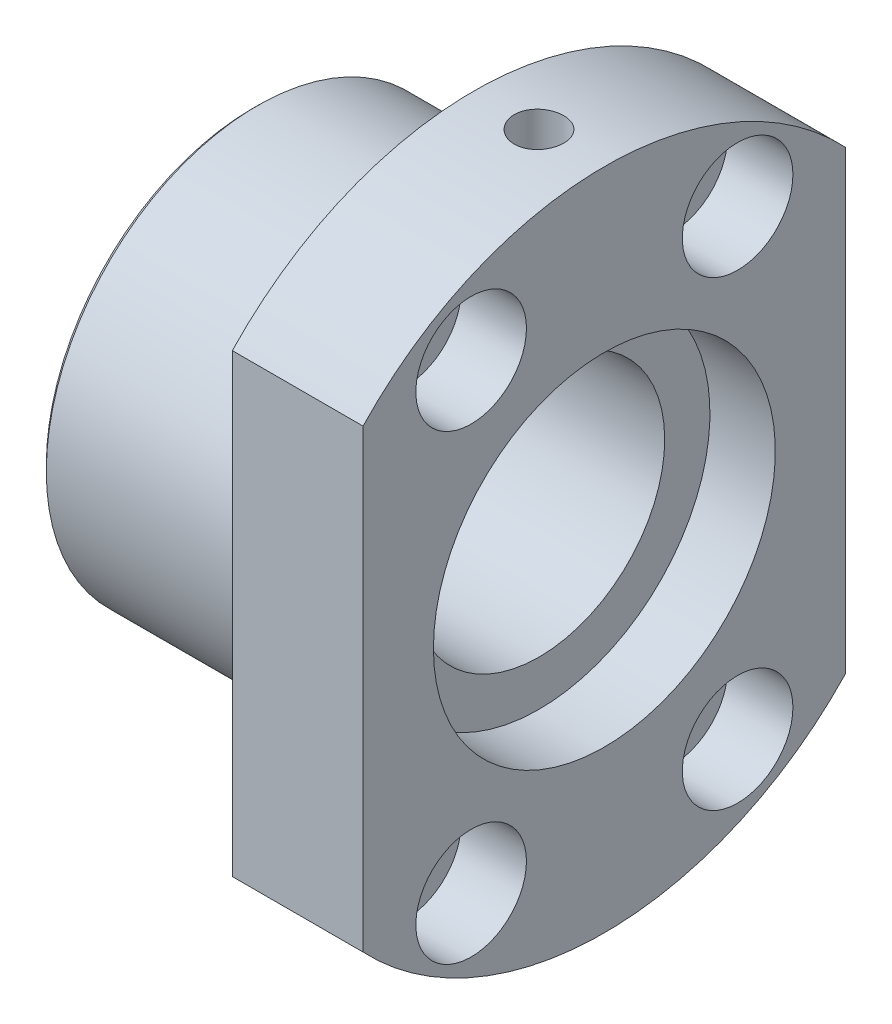
SolidWorks part; units mm, degrees
ref_plane "Front Plane" through (0, 0, 0) normal (0, 0, 1) x (1, 0, 0)
ref_plane "Top Plane" through (0, 0, 0) normal (0, 1, 0) x (1, 0, 0)
ref_plane "Right Plane" through (0, 0, 0) normal (1, 0, 0) x (0, 0, -1)
sketch "Sketch1" plane through (0, 0, 0) normal (0, 0, 1) x (1, 0, 0)
  line L0 (6.5, 17) -> (6.5, 12.5)
  line L1 (-22, 0) -> (13, 0) construction
  line L3 (-17, 12.5) -> (6.5, 12.5)
  line L4 (13, 33) -> (0, 33)
  line L5 (0, 33) -> (0, 21)
  line L6 (0, 21) -> (-22, 21)
  line L8 (-22, 21) -> (-22, 17)
  line L9 (-22, 17) -> (-17, 17)
  line L10 (-17, 17) -> (-17, 12.5)
  line L11 (6.5, 17) -> (13, 17)
  line L12 (13, 17) -> (13, 33)
revolve "Revolve1" add sketch "Sketch1" angle 360 about L1
sketch "Sketch2" plane through (0, 0, 0) normal (1, 0, 0) x (0, 0, -1)
  line L0 (24, 22.6495) -> (24, -22.6495)
  line L1 (-24, 22.6495) -> (-24, -22.6495)
  arc A0 (24, -22.6495) -> (24, 22.6495) centre (0, 0) ccw
  arc A2 (-24, 22.6495) -> (-24, -22.6495) centre (0, 0) ccw
extrude "Cut-Extrude1" cut sketch "Sketch2" along normal through all
hole_wizard "Socket Head Cap Screw1" positions "Sketch4" profile "Sketch3" counterbore size "M2" standard "JIS" end condition through all
sketch "Sketch4" plane through (13, 0, 0) normal (1, 0, 0) x (0, 0, -1)
  point P5 (-13.25, 22.9497)
  point P6 (13.25, -22.9497)
  point P7 (-13.25, -22.9497)
  point P8 (13.25, 22.9497)
sketch "Sketch3" plane through (13, 22.9497, 13.25) normal (0, 1, 0) x (0, 0, -1)
  line L0 (0, 0) -> (0, 35)
  line L1 (0, 35) -> (3.3, 35)
  line L3 (3.3, 35) -> (3.3, 6.5)
  line L4 (3.3, 6.5) -> (5.5, 6.5)
  line L5 (5.5, 6.5) -> (5.5, 0)
  line L7 (5.5, 0) -> (0, 0)
  line L11 (0, -6.35) -> (0, 107.95) construction
  dimension "Thru Hole Dia." = 6.6
  dimension "Thru Hole Depth" = 35
  dimension "C'Bore Dia." = 11
  dimension "C'Bore Depth" = 6.5
ref_plane "Plane1" through (0, 33, 0) normal (0, 1, 0) x (1, 0, 0)
hole_wizard "Tap1" positions "Sketch6" profile "Sketch5" hole size "M10x1.5" standard "JIS"
sketch "Sketch6" plane through (0, 33, 0) normal (0, 1, 0) x (1, 0, 0)
  point P0 (6.5, 0)
sketch "Sketch5" plane through (6.5, 33, 0) normal (1, 0, 0) x (0, 0, 1)
  line L0 (0, 0) -> (0, 34.4762)
  line L1 (0, 34.4762) -> (2.4585, 32.999)
  line L2 (2.4585, 32.999) -> (2.4585, 0)
  line L5 (2.4585, 0) -> (0, 0)
  line L10 (0, 34.4762) -> (-2.4585, 32.999) construction
  line L11 (0, -6.35) -> (0, 107.95) construction
  dimension "Hole Dia." = 4.917
  dimension "Hole Depth" = 32.999
  dimension "Drill Angle" = 118
cosmetic thread "Thread1" parameters "NFIX_2"=8, "NFIX_1"=6
chamfer "Chamfer1" distance 0.5 1 edges at (-22, 0, 21)
